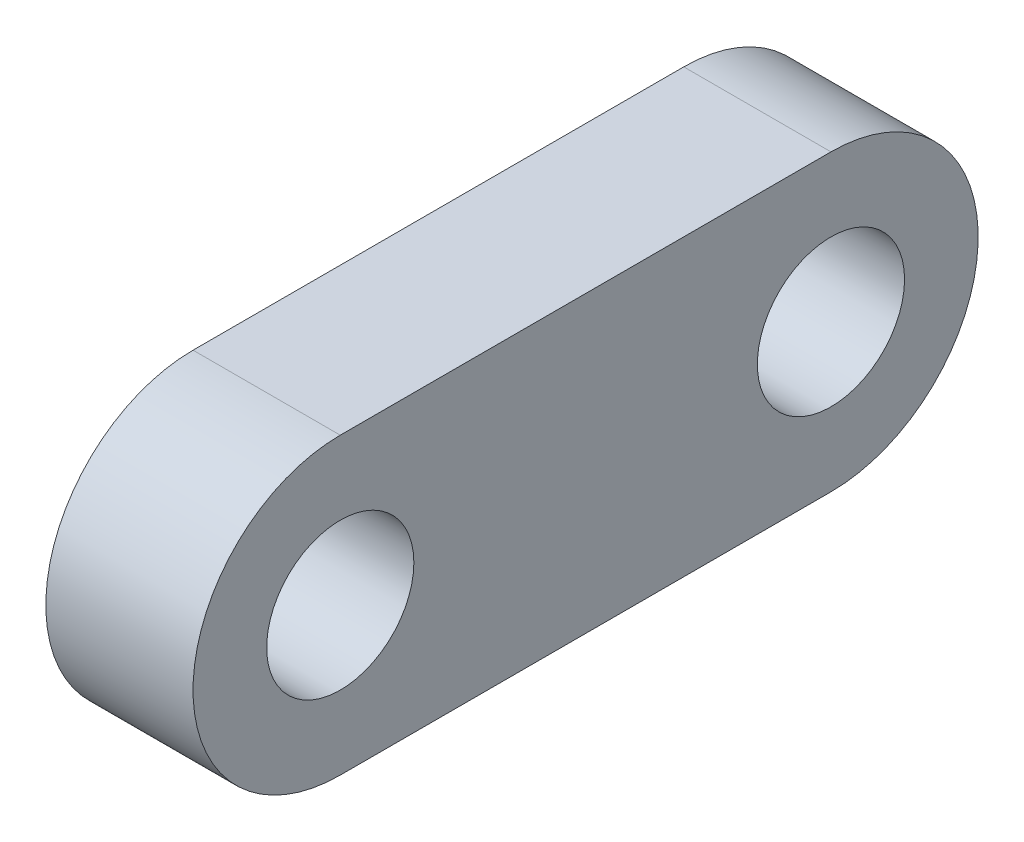
SolidWorks part; units mm, degrees
ref_plane "前视基准面" through (0, 0, 0) normal (0, 0, 1) x (1, 0, 0)
ref_plane "上视基准面" through (0, 0, 0) normal (0, 1, 0) x (1, 0, 0)
ref_plane "右视基准面" through (0, 0, 0) normal (1, 0, 0) x (0, 0, -1)
other "Configuration Table"
sketch "草图1" plane through (0, 0, 0) normal (1, 0, 0) x (0, 0, -1)
  line L0 (0, 4.5) -> (10, 4.5)
  line L5 (0, -1.5) -> (10, -1.5)
  circle A0 centre (0, 1.5) radius 1.5
  circle A1 centre (10, 1.5) radius 1.5
  arc A2 (0, 4.5) -> (0, -1.5) centre (0, 1.5) ccw
  arc A3 (10, -1.5) -> (10, 4.5) centre (10, 1.5) ccw
  dimension "D1" = 10
  dimension "D2" = 3
  dimension "D3" = 3
extrude "凸台-拉伸1" add sketch "草图1" along normal blind 3
